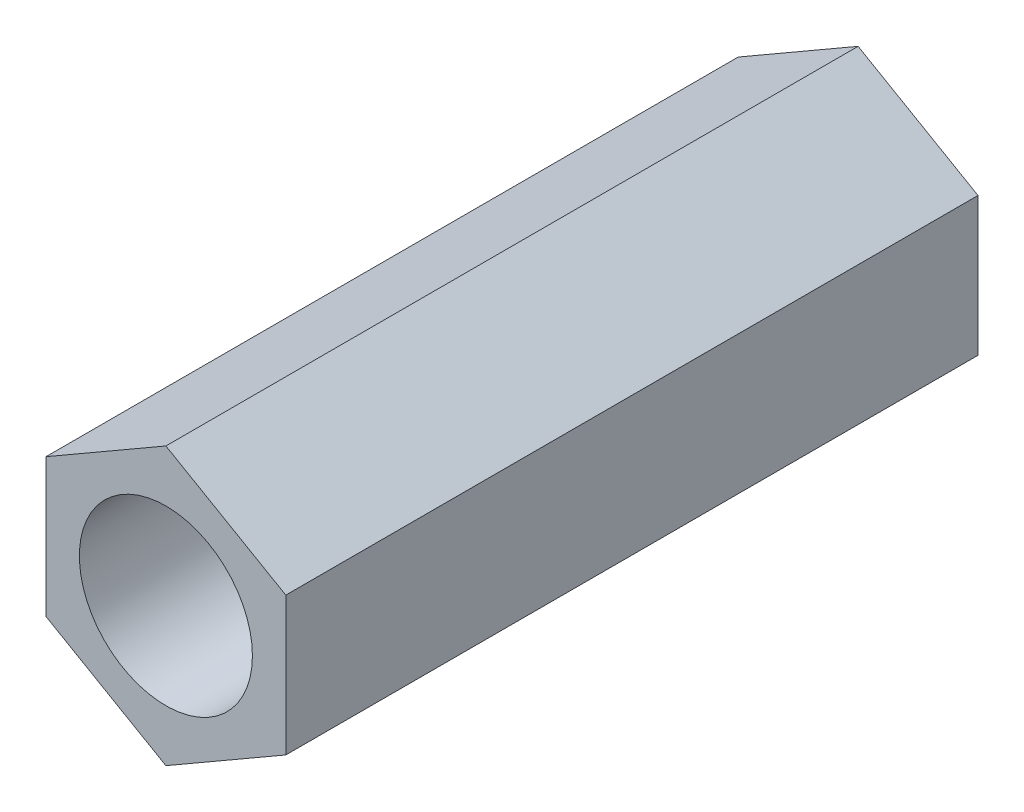
SolidWorks part; units mm, degrees
ref_plane "Front Plane" through (0, 0, 0) normal (0, 0, 1) x (1, 0, 0)
ref_plane "Top Plane" through (0, 0, 0) normal (0, 1, 0) x (1, 0, 0)
ref_plane "Right Plane" through (0, 0, 0) normal (1, 0, 0) x (0, 0, -1)
sketch "Sketch1" plane through (0, 0, 0) normal (0, 0, 1) x (1, 0, 0)
  line L1 (0, 0.4) -> (-0.3464, 0.2)
  line L2 (-0.3464, 0.2) -> (-0.3464, -0.2)
  line L3 (-0.3464, -0.2) -> (0, -0.4)
  line L4 (0, -0.4) -> (0.3464, -0.2)
  line L5 (0.3464, -0.2) -> (0.3464, 0.2)
  line L6 (0.3464, 0.2) -> (0, 0.4)
  circle A0 centre (0, 0) radius 0.3464 construction
  circle A1 centre (0, 0) radius 0.25
  dimension "D1" = 0.5
  dimension "D2" = 0.8
extrude "Boss-Extrude1" add sketch "Sketch1" along normal blind 2
